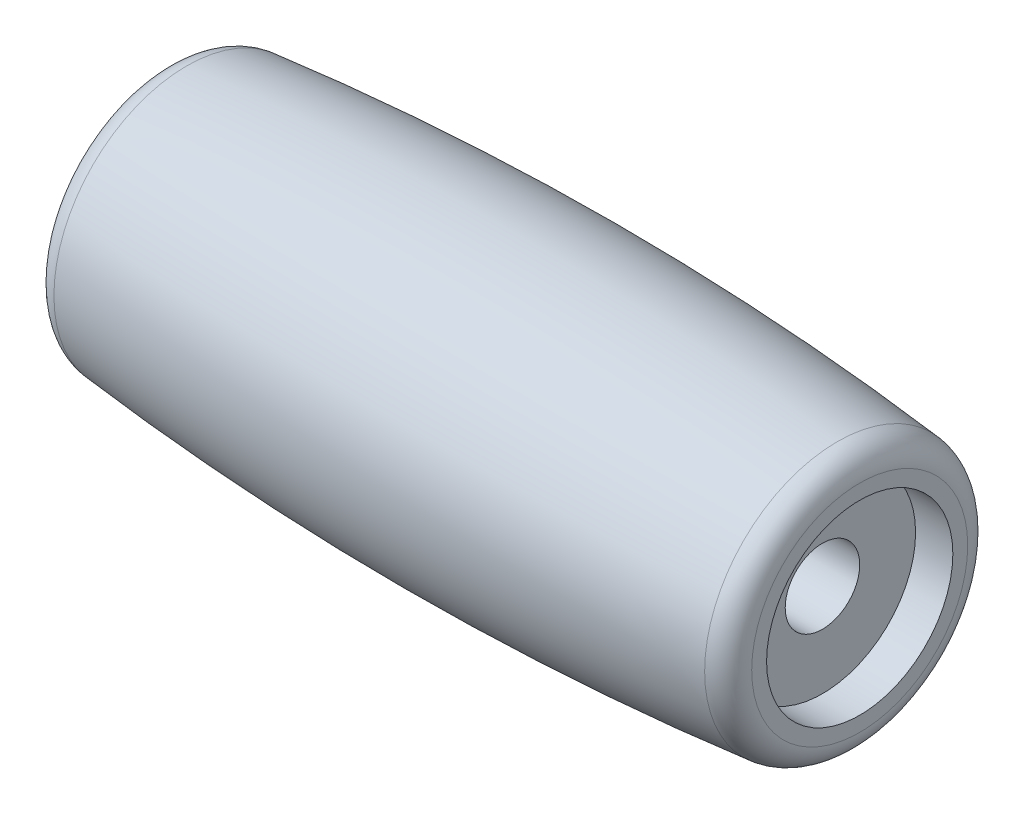
SolidWorks part; units mm, degrees
ref_plane "Front Plane" through (0, 0, 0) normal (0, 0, 1) x (1, 0, 0)
ref_plane "Top Plane" through (0, 0, 0) normal (0, 1, 0) x (1, 0, 0)
ref_plane "Right Plane" through (0, 0, 0) normal (1, 0, 0) x (0, 0, -1)
sketch "Sketch1" plane through (0, 0, 0) normal (0, 0, 1) x (1, 0, 0)
  line L0 (0, 6) -> (0, 0) construction
  line L1 (0, 0) -> (110.2595, 0) construction
  line L2 (-12.5, 1.5) -> (12.5, 1.5)
  line L3 (12.5, 1.5) -> (12.5, 3.75)
  line L4 (12.5, 3.75) -> (14, 3.75)
  line L5 (14, 3.75) -> (14, 4.3486)
  line L6 (-14, 3.75) -> (-14, 4.3486)
  line L7 (-12.5, 3.75) -> (-14, 3.75)
  line L8 (-12.5, 1.5) -> (-12.5, 3.75)
  arc A0 (-13.1, 5.3436) -> (13.1, 5.3436) centre (0, -125.0417) cw
  arc A1 (14, 4.3486) -> (13.1, 5.3436) centre (13, 4.3486) ccw
  arc A2 (-14, 4.3486) -> (-13.1, 5.3436) centre (-13, 4.3486) cw
  point P13 (0, 1.5)
  point P16 (14, 5.25)
  point P19 (-14, 5.25)
  dimension "D7" = 1
  dimension "D1" = 1.5
  dimension "D2" = 3.75
  dimension "D3" = 1.5
  dimension "D4" = 1.5
  dimension "D5" = 14
  dimension "D6" = 6
revolve "Revolve1" add sketch "Sketch1" angle 360 about L1
